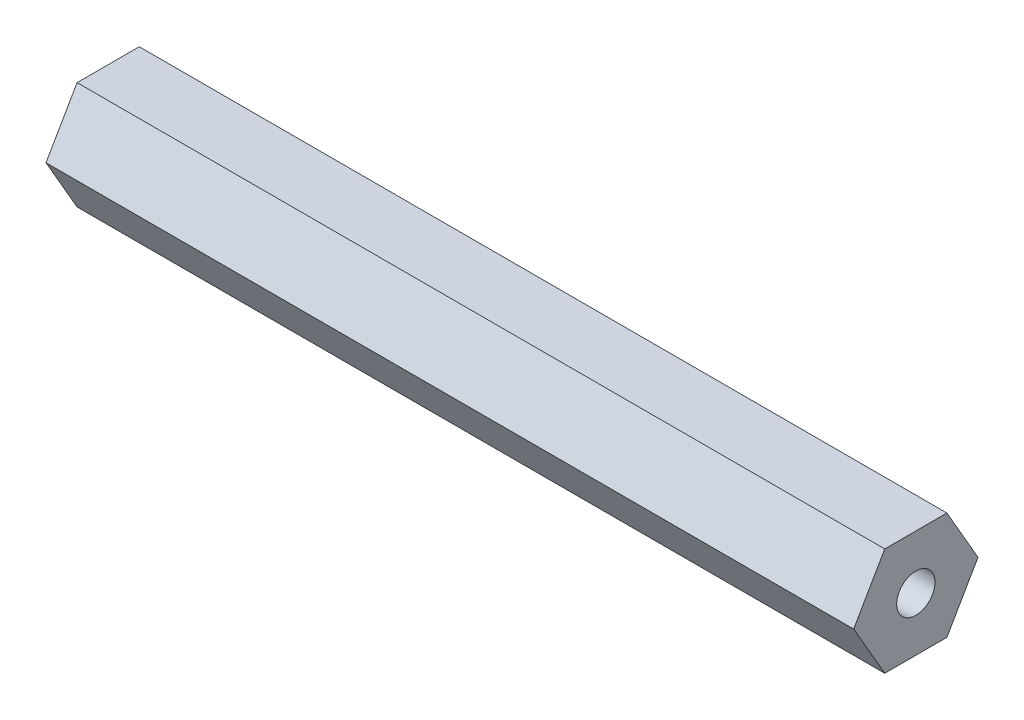
SolidWorks part; units mm, degrees
material "6061 Alloy"
ref_plane "Front Plane" through (0, 0, 0) normal (0, 0, 1) x (1, 0, 0)
ref_plane "Top Plane" through (0, 0, 0) normal (0, 1, 0) x (1, 0, 0)
ref_plane "Right Plane" through (0, 0, 0) normal (1, 0, 0) x (0, 0, -1)
sketch "Sketch1" plane through (0, 0, 0) normal (1, 0, 0) x (0, 0, -1)
  line L1 (3.6662, 0) -> (1.8331, 3.175)
  line L2 (1.8331, 3.175) -> (-1.8331, 3.175)
  line L3 (-1.8331, 3.175) -> (-3.6662, 0)
  line L4 (-3.6662, 0) -> (-1.8331, -3.175)
  line L5 (-1.8331, -3.175) -> (1.8331, -3.175)
  line L6 (1.8331, -3.175) -> (3.6662, 0)
  circle A0 centre (0, 0) radius 3.175 construction
  dimension "D1" = 6.35
extrude "Extrude1" add sketch "Sketch1" against normal blind 47.625
hole_wizard "#4-40 Tapped Hole1" positions "Sketch3" profile "Sketch2" tap size "#4-40" standard "Ansi Inch"
sketch "Sketch3" plane through (0, 0, 0) normal (1, 0, 0) x (0, 0, -1)
  point P0 (0, 0)
sketch "Sketch2" plane through (0, 0, 0) normal (0, 1, 0) x (0, 0, -1)
  line L0 (0, 0) -> (0, 9.5438)
  line L1 (0, 9.5438) -> (1.1303, 8.8646)
  line L2 (1.1303, 8.8646) -> (1.1303, 0)
  line L5 (1.1303, 0) -> (0, 0)
  line L10 (0, 9.5438) -> (-1.1303, 8.8646) construction
  line L11 (0, -6.35) -> (0, 107.95) construction
  dimension "Tap Drill Dia." = 2.2606
  dimension "Tap Drill Depth" = 8.8646
  dimension "Drill Angle" = 118
cosmetic thread "Hole Thread1" parameters "D1"=5.6896, "D2"=2.8448
hole_wizard "#4-40 Tapped Hole2" positions "Sketch5" profile "Sketch4" tap size "#4-40" standard "Ansi Inch"
sketch "Sketch5" plane through (-47.625, 0, 0) normal (-1, 0, 0) x (0, 0, 1)
  point P0 (0, 0)
sketch "Sketch4" plane through (-47.625, 0, 0) normal (0, 1, 0) x (0, 0, 1)
  line L0 (0, 0) -> (0, 9.5438)
  line L1 (0, 9.5438) -> (1.1303, 8.8646)
  line L2 (1.1303, 8.8646) -> (1.1303, 0)
  line L5 (1.1303, 0) -> (0, 0)
  line L10 (0, 9.5438) -> (-1.1303, 8.8646) construction
  line L11 (0, -6.35) -> (0, 107.95) construction
  dimension "Tap Drill Dia." = 2.2606
  dimension "Tap Drill Depth" = 8.8646
  dimension "Drill Angle" = 118
cosmetic thread "Hole Thread2" parameters "D1"=5.6896, "D2"=2.8448
